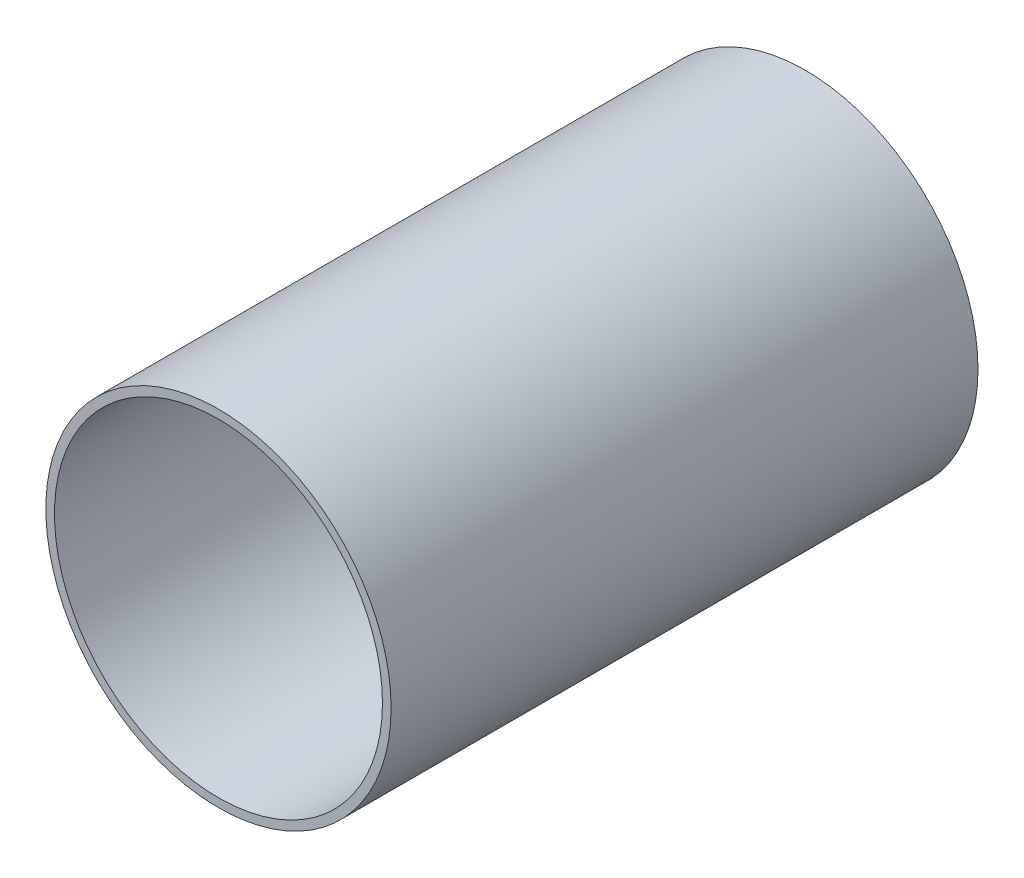
SolidWorks part; units mm, degrees
ref_plane "Front Plane" through (0, 0, 0) normal (0, 0, 1) x (1, 0, 0)
ref_plane "Top Plane" through (0, 0, 0) normal (0, 1, 0) x (1, 0, 0)
ref_plane "Right Plane" through (0, 0, 0) normal (1, 0, 0) x (0, 0, -1)
sketch "Sketch1" plane through (0, 0, 0) normal (0, 0, 1) x (1, 0, 0)
  circle A0 centre (0, 0) radius 10
  dimension "D1" = 20
extrude "Boss-Extrude1" add sketch "Sketch1" along normal blind 1
sketch "Sketch2" plane through (0, 0, 1) normal (0, 0, 1) x (1, 0, 0)
  circle A0 centre (0, 0) radius 10
  circle A1 centre (0, 0) radius 9.5
  circle A2 centre (0, 0) radius 10 construction
  dimension "D1" = 0.5
extrude "Boss-Extrude2" add sketch "Sketch2" along normal blind 33
chamfer "Chamfer1" distance 1 angle 45 1 edges at (9.5, 0, 1)
